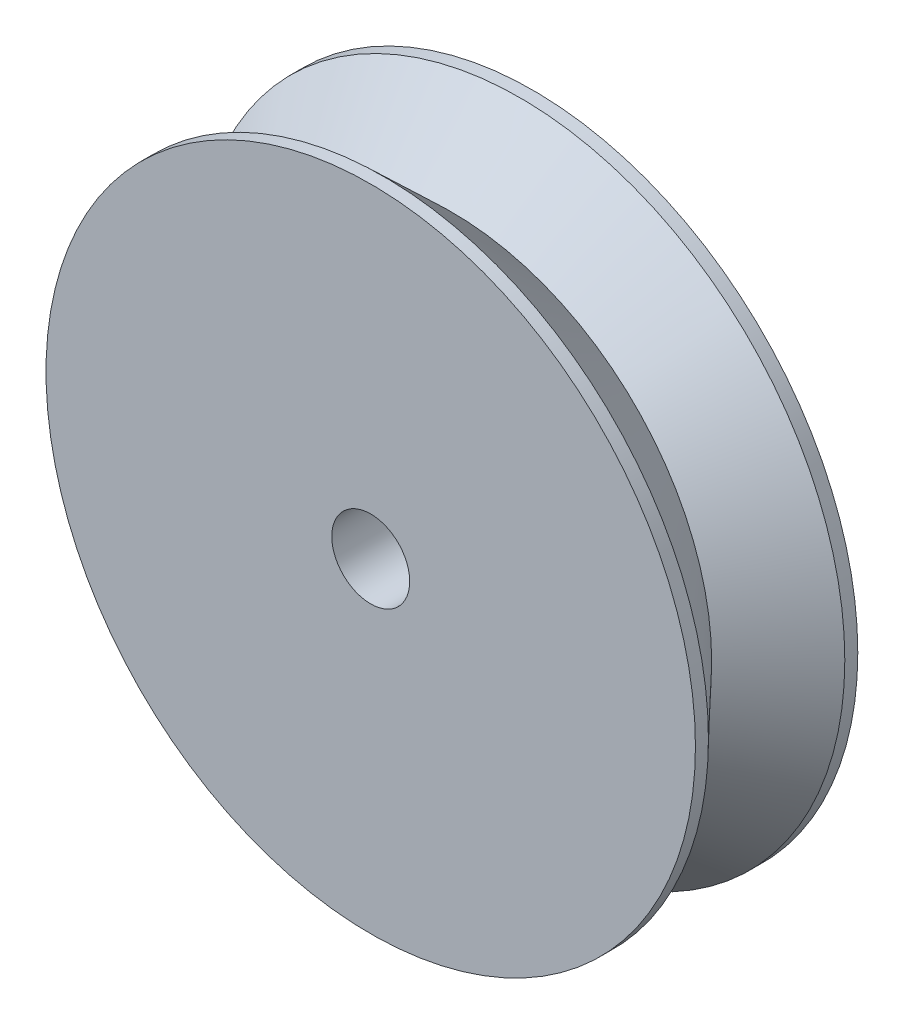
SolidWorks part; units mm, degrees
ref_plane "Front Plane" through (0, 0, 0) normal (0, 0, 1) x (1, 0, 0)
ref_plane "Top Plane" through (0, 0, 0) normal (0, 1, 0) x (1, 0, 0)
ref_plane "Right Plane" through (0, 0, 0) normal (1, 0, 0) x (0, 0, -1)
sketch "Sketch1" plane through (0, 0, 0) normal (1, 0, 0) x (0, 0, -1)
  line L0 (0, 0) -> (6.35, 0)
  line L1 (6.35, 0) -> (6.35, 12.7)
  line L2 (0, 12.7) -> (0.508, 12.7)
  line L3 (0.508, 12.7) -> (3.175, 10.16)
  line L4 (0, 12.7) -> (0, 0)
  line L5 (3.175, 10.16) -> (5.842, 12.7)
  line L6 (5.842, 12.7) -> (6.35, 12.7)
  dimension "D1" = 6.35
  dimension "D2" = 12.7
  dimension "D3" = 12.7
  dimension "D4" = 0.508
  dimension "D5" = 0.508
  dimension "D6" = 10.16
  dimension "D7" = 3.175
revolve "Revolve1" add sketch "Sketch1" angle 360 about L0
sketch "Sketch3" plane through (0, 0, 0) normal (0, 0, 1) x (1, 0, 0)
  circle A0 centre (0, 0) radius 1.524
extrude "Cut-Extrude1" cut sketch "Sketch3" against normal through all
